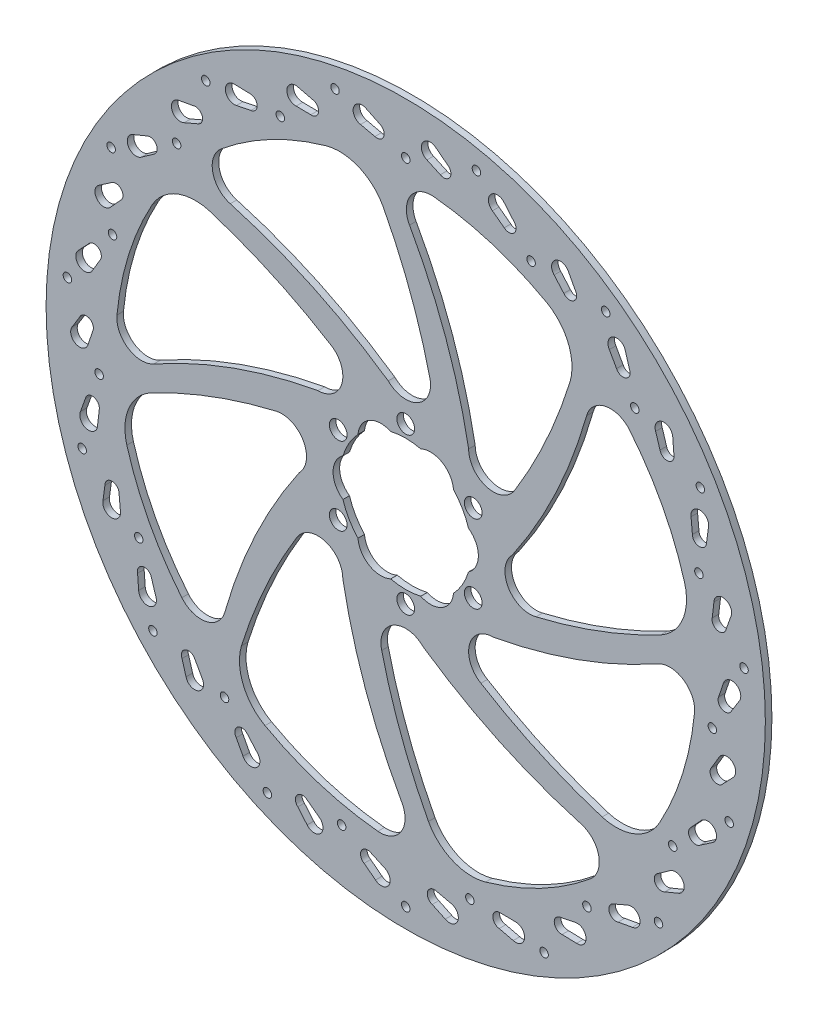
SolidWorks part; units mm, degrees
material "Chrome Stainless Steel"
ref_plane "Plan de face" through (0, 0, 0) normal (0, 0, 1) x (1, 0, 0)
ref_plane "Plan de dessus" through (0, 0, 0) normal (0, 1, 0) x (1, 0, 0)
ref_plane "Plan de droite" through (0, 0, 0) normal (1, 0, 0) x (0, 0, -1)
sketch "Sketch1" plane through (0, 0, 0) normal (0, 0, 1) x (1, 0, 0)
  line L0 (11.7494, 91.2536) -> (8.3288, 93.8934)
  line L1 (9.7648, 87.7806) -> (5.9882, 89.5132)
  line L2 (30.4653, 86.8166) -> (27.6683, 90.1099)
  line L3 (27.8021, 83.8322) -> (24.4682, 86.3121)
  line L4 (-7.48, 91.7023) -> (-11.3747, 93.5732)
  line L5 (47.8498, 78.5854) -> (45.7986, 82.3882)
  line L6 (44.6242, 76.2198) -> (41.8788, 79.3388)
  line L7 (-8.6992, 87.8926) -> (-12.7535, 88.8022)
  line L8 (63.143, 66.9196) -> (61.9273, 71.0658)
  line L9 (59.4961, 65.2764) -> (57.4591, 68.898)
  line L10 (75.6765, 52.329) -> (75.3494, 56.6374)
  line L11 (71.7677, 51.48) -> (70.5282, 55.446)
  line L12 (84.9026, 35.4515) -> (85.4784, 39.7337)
  line L13 (80.9026, 35.4337) -> (80.5148, 39.5707)
  line L14 (90.4181, 17.0245) -> (91.8716, 21.0935)
  line L15 (86.5018, 17.8388) -> (86.9826, 21.966)
  line L16 (91.9818, -2.1465) -> (94.2496, 1.5314)
  line L17 (88.3204, -0.5358) -> (89.6488, 3.4013)
  line L18 (89.5255, -21.2236) -> (92.5084, -18.0977)
  line L19 (86.279, -18.8869) -> (88.3969, -15.3121)
  line L20 (83.1565, -39.3733) -> (86.7242, -36.9358)
  line L21 (80.4668, -36.4126) -> (83.2817, -33.3562)
  line L22 (73.1532, -55.8021) -> (77.1496, -54.1596)
  line L23 (71.1378, -52.3469) -> (74.5266, -49.9425)
  line L24 (59.9527, -69.7921) -> (64.2033, -69.0164)
  line L25 (58.6997, -65.9934) -> (62.5144, -64.3461)
  line L26 (44.132, -80.7318) -> (48.451, -80.8569)
  line L27 (43.6962, -76.7556) -> (47.77, -75.9375)
  line L28 (26.3825, -88.1432) -> (30.5811, -89.1635)
  line L29 (26.783, -84.1633) -> (30.9378, -84.21)
  line L30 (7.48, -91.7023) -> (11.3747, -93.5732)
  line L31 (8.6992, -87.8926) -> (12.7535, -88.8022)
  line L32 (-11.7494, -91.2536) -> (-8.3288, -93.8934)
  line L33 (-9.7648, -87.7806) -> (-5.9882, -89.5132)
  line L34 (-30.4653, -86.8166) -> (-27.6683, -90.1099)
  line L35 (-27.8021, -83.8322) -> (-24.4682, -86.3121)
  line L36 (-47.8498, -78.5854) -> (-45.7986, -82.3882)
  line L37 (-44.6242, -76.2198) -> (-41.8788, -79.3388)
  line L38 (-63.143, -66.9196) -> (-61.9273, -71.0658)
  line L39 (-59.4961, -65.2764) -> (-57.4591, -68.898)
  line L40 (-75.6765, -52.329) -> (-75.3494, -56.6374)
  line L41 (-71.7677, -51.48) -> (-70.5282, -55.446)
  line L42 (-84.9026, -35.4515) -> (-85.4784, -39.7337)
  line L43 (-80.9026, -35.4337) -> (-80.5148, -39.5707)
  line L44 (-90.4181, -17.0245) -> (-91.8716, -21.0935)
  line L45 (-86.5018, -17.8388) -> (-86.9826, -21.966)
  line L46 (-91.9818, 2.1465) -> (-94.2496, -1.5314)
  line L47 (-88.3204, 0.5358) -> (-89.6488, -3.4013)
  line L48 (-89.5255, 21.2236) -> (-92.5084, 18.0977)
  line L49 (-86.279, 18.8869) -> (-88.3969, 15.3121)
  line L50 (-83.1565, 39.3733) -> (-86.7242, 36.9358)
  line L51 (-80.4668, 36.4126) -> (-83.2817, 33.3562)
  line L52 (-73.1532, 55.8021) -> (-77.1496, 54.1596)
  line L53 (-71.1378, 52.3469) -> (-74.5266, 49.9425)
  line L54 (-59.9527, 69.7921) -> (-64.2033, 69.0164)
  line L55 (-58.6997, 65.9934) -> (-62.5144, 64.3461)
  line L56 (-44.132, 80.7318) -> (-48.451, 80.8569)
  line L57 (-43.6962, 76.7556) -> (-47.77, 75.9375)
  line L58 (-26.3825, 88.1432) -> (-30.5811, 89.1635)
  line L59 (-26.783, 84.1633) -> (-30.9378, 84.21)
  line L60 (0, 18.97) -> (0, 25.9709) construction
  line L61 (0, 0) -> (0, 18.5) construction
  line L62 (0, 0) -> (7, 12.1244) construction
  circle A0 centre (0, 0) radius 101.5
  circle A3 centre (0, 0) radius 14 construction
  circle A4 centre (0, 0) radius 22 construction
  circle A5 centre (0, 22) radius 2.5
  circle A8 centre (19.0526, 11) radius 2.5
  arc A10 (-4.2376, 18.0081) -> (-13.4767, 12.6739) centre (-7, 12.1244) ccw
  arc A12 (13.4767, 12.6739) -> (4.2375, 18.0081) centre (7, 12.1244) ccw
  arc A13 (4.2375, 18.0081) -> (-4.2376, 18.0081) centre (0, 0) ccw
  circle A14 centre (19.0526, -11) radius 2.5
  circle A15 centre (0, -22) radius 2.5
  circle A16 centre (0, -96) radius 1.2
  circle A17 centre (-19.0526, -11) radius 2.5
  circle A18 centre (-19.0526, 11) radius 2.5
  arc A19 (17.7143, 5.3342) -> (13.4767, 12.6739) centre (0, 0) ccw
  arc A20 (-13.4767, 12.6739) -> (-17.7143, 5.3342) centre (0, 0) ccw
  arc A21 (-49.5229, 51.0449) -> (-4.9497, 30.0502) centre (-90.2856, -93.3102) cw
  arc A22 (17.7487, 24.7487) -> (30.7822, 21.1994) centre (24.7487, 24.7487) ccw
  circle A23 centre (-39.0467, -87.7004) radius 1.2
  arc A24 (-22.5455, 78.7108) -> (-52.0725, 63.1834) centre (0, 0) ccw
  arc A25 (46.3594, 55.4206) -> (39.7148, 71.599) centre (32.924, 59.3563) ccw
  arc A26 (46.3594, 55.4206) -> (30.7822, 21.1994) centre (-96.8744, 99.9637) cw
  arc A27 (7.8566, 81.4983) -> (1.0763, 71.1122) centre (7.1849, 74.5306) ccw
  arc A28 (-6.4072, 71.9693) -> (6.776, 36.7565) centre (-139.1855, 2.1845) cw
  arc A29 (39.7148, 71.599) -> (7.8566, 81.4983) centre (0, 0) ccw
  arc A30 (1.0763, 71.1122) -> (17.7487, 24.7487) centre (-129.8218, -2.1387) cw
  arc A31 (17.7143, -5.3342) -> (17.7143, 5.3342) centre (14, 0) ccw
  circle A32 centre (-71.3419, -64.2365) radius 1.2
  arc A33 (-63.1834, -52.0725) -> (-51.0449, -49.5229) centre (-57.7815, -47.6206) ccw
  arc A34 (-6.4072, 71.9693) -> (-22.5455, 78.7108) centre (-18.6905, 65.252) ccw
  arc A35 (78.7108, 22.5455) -> (63.1834, 52.0725) centre (0, 0) ccw
  arc A36 (-17.7487, -24.7487) -> (-30.7822, -21.1994) centre (-24.7487, -24.7487) ccw
  arc A37 (4.9497, -30.0503) -> (-6.776, -36.7565) centre (0, -35) ccw
  arc A38 (6.4072, -71.9693) -> (22.5455, -78.7108) centre (18.6905, -65.252) ccw
  arc A39 (6.4072, -71.9693) -> (-6.776, -36.7565) centre (139.1855, -2.1845) cw
  arc A40 (22.5455, -78.7108) -> (52.0725, -63.1834) centre (0, 0) ccw
  arc A41 (-52.0725, 63.1834) -> (-49.5229, 51.0449) centre (-47.6206, 57.7815) ccw
  arc A42 (-4.9497, 30.0502) -> (6.776, 36.7565) centre (0, 35) ccw
  arc A43 (63.1834, 52.0725) -> (51.0449, 49.5229) centre (57.7815, 47.6206) ccw
  arc A44 (13.4767, -12.6739) -> (17.7143, -5.3342) centre (0, 0) ccw
  circle A45 centre (-91.3014, -29.6656) radius 1.2
  circle A46 centre (-95.4741, 10.0347) radius 1.2
  circle A47 centre (-83.1384, 48) radius 1.2
  circle A48 centre (-56.4274, 77.6656) radius 1.2
  circle A49 centre (-19.9595, 93.9022) radius 1.2
  circle A50 centre (19.9595, 93.9022) radius 1.2
  circle A51 centre (56.4274, 77.6656) radius 1.2
  arc A52 (51.0449, 49.5229) -> (30.0502, 4.9497) centre (-93.3102, 90.2856) cw
  arc A53 (30.0502, 4.9497) -> (36.7565, -6.776) centre (35, 0) ccw
  arc A54 (71.9693, 6.4072) -> (78.7108, 22.5455) centre (65.252, 18.6905) ccw
  arc A55 (4.2376, -18.0081) -> (13.4767, -12.6739) centre (7, -12.1244) ccw
  arc A56 (71.9693, 6.4072) -> (36.7565, -6.776) centre (2.1845, 139.1855) cw
  arc A57 (55.4206, -46.3594) -> (71.599, -39.7148) centre (59.3563, -32.924) ccw
  arc A58 (55.4206, -46.3594) -> (21.1994, -30.7822) centre (99.9637, 96.8744) cw
  arc A59 (24.7487, -17.7487) -> (21.1994, -30.7822) centre (24.7487, -24.7487) ccw
  arc A60 (81.4983, -7.8566) -> (71.1122, -1.0763) centre (74.5306, -7.1849) ccw
  arc A61 (71.599, -39.7148) -> (81.4983, -7.8566) centre (0, 0) ccw
  arc A62 (71.1122, -1.0763) -> (24.7487, -17.7487) centre (-2.1387, 129.8218) cw
  arc A63 (-4.2376, -18.0081) -> (4.2376, -18.0081) centre (0, 0) ccw
  circle A64 centre (83.1384, 48) radius 1.2
  circle A65 centre (95.4741, 10.0347) radius 1.2
  circle A66 centre (91.3014, -29.6656) radius 1.2
  circle A67 centre (71.3419, -64.2365) radius 1.2
  circle A68 centre (39.0467, -87.7004) radius 1.2
  arc A69 (-55.4206, 46.3594) -> (-21.1994, 30.7821) centre (-99.9637, -96.8744) cw
  arc A70 (-71.599, 39.7148) -> (-81.4983, 7.8566) centre (0, 0) ccw
  arc A71 (-71.9693, -6.4072) -> (-78.7108, -22.5455) centre (-65.252, -18.6905) ccw
  arc A72 (-24.7487, 17.7487) -> (-21.1994, 30.7821) centre (-24.7487, 24.7487) ccw
  circle A73 centre (18.0883, -85.0988) radius 1.2
  arc A74 (49.5229, -51.045) -> (4.9497, -30.0503) centre (90.2856, 93.3102) cw
  arc A75 (-13.4767, -12.6739) -> (-4.2376, -18.0081) centre (-7, -12.1244) ccw
  arc A76 (52.0725, -63.1834) -> (49.5229, -51.045) centre (47.6206, -57.7815) ccw
  arc A77 (-46.3594, -55.4206) -> (-30.7822, -21.1994) centre (96.8744, -99.9637) cw
  arc A78 (-46.3594, -55.4206) -> (-39.7148, -71.599) centre (-32.924, -59.3563) ccw
  arc A79 (-39.7148, -71.599) -> (-7.8566, -81.4983) centre (0, 0) ccw
  arc A80 (-1.0763, -71.1122) -> (-17.7487, -24.7487) centre (129.8218, 2.1387) cw
  arc A81 (-7.8566, -81.4983) -> (-1.0763, -71.1122) centre (-7.1849, -74.5306) ccw
  arc A82 (-17.7143, -5.3342) -> (-13.4767, -12.6739) centre (0, 0) ccw
  arc A83 (-78.7108, -22.5455) -> (-63.1834, -52.0725) centre (0, 0) ccw
  arc A84 (-71.9693, -6.4072) -> (-36.7565, 6.776) centre (-2.1845, -139.1855) cw
  arc A85 (-51.0449, -49.5229) -> (-30.0502, -4.9497) centre (93.3102, -90.2856) cw
  arc A86 (-30.0502, -4.9497) -> (-36.7565, 6.776) centre (-35, 0) ccw
  arc A87 (-17.7143, 5.3342) -> (-17.7143, -5.3342) centre (-14, 0) ccw
  arc A88 (-81.4983, 7.8566) -> (-71.1122, 1.0763) centre (-74.5306, 7.1849) ccw
  arc A89 (-55.4206, 46.3594) -> (-71.599, 39.7148) centre (-59.3563, 32.924) ccw
  arc A91 (-71.1122, 1.0763) -> (-24.7487, 17.7487) centre (2.1387, -129.8218) cw
  circle A92 centre (-18.0883, -85.0988) radius 1.2
  circle A93 centre (-51.1373, -70.3845) radius 1.2
  circle A94 centre (-75.3442, -43.5) radius 1.2
  circle A95 centre (-86.5234, -9.094) radius 1.2
  circle A96 centre (-82.7419, 26.8845) radius 1.2
  circle A97 centre (-64.6536, 58.2144) radius 1.2
  circle A98 centre (-35.3861, 79.4785) radius 1.2
  circle A99 centre (0, 87) radius 1.2
  circle A100 centre (35.3861, 79.4785) radius 1.2
  circle A101 centre (64.6536, 58.2144) radius 1.2
  circle A102 centre (82.7419, 26.8845) radius 1.2
  circle A103 centre (86.5234, -9.094) radius 1.2
  circle A104 centre (75.3442, -43.5) radius 1.2
  circle A105 centre (51.1373, -70.3845) radius 1.2
  arc A106 (9.7648, 87.7806) -> (11.7494, 91.2536) centre (10.7571, 89.5171) ccw
  arc A107 (-8.6992, 87.8926) -> (-7.48, 91.7023) centre (-8.0896, 89.7975) ccw
  arc A108 (-11.1479, 93.4643) -> (-12.7535, 88.8022) centre (-12.3425, 91.2681) ccw
  arc A109 (8.528, 93.7396) -> (5.9882, 89.5132) centre (6.9029, 91.8399) ccw
  arc A110 (27.8021, 83.8322) -> (30.4653, 86.8166) centre (29.1337, 85.3244) ccw
  arc A111 (27.8312, 89.9181) -> (24.4682, 86.3121) centre (25.8467, 88.3977) ccw
  arc A112 (44.6242, 76.2198) -> (47.8498, 78.5854) centre (46.237, 77.4026) ccw
  arc A113 (45.9181, 82.1668) -> (41.8788, 79.3388) centre (43.6608, 81.0922) ccw
  arc A114 (59.4961, 65.2764) -> (63.143, 66.9196) centre (61.3195, 66.098) ccw
  arc A115 (61.9981, 70.8243) -> (57.4591, 68.898) centre (59.5667, 70.2426) ccw
  arc A116 (71.7677, 51.48) -> (75.6765, 52.329) centre (73.7221, 51.9045) ccw
  arc A117 (75.3685, 56.3865) -> (70.5282, 55.446) centre (72.8693, 56.323) ccw
  arc A118 (80.9026, 35.4337) -> (84.9026, 35.4515) centre (82.9026, 35.4426) ccw
  arc A119 (85.4449, 39.4844) -> (80.5148, 39.5707) centre (82.9871, 39.9418) ccw
  arc A120 (86.5018, 17.8388) -> (90.4181, 17.0245) centre (88.4599, 17.4317) ccw
  arc A121 (91.787, 20.8565) -> (86.9826, 21.966) centre (89.478, 21.815) ccw
  arc A122 (88.3204, -0.5358) -> (91.9818, -2.1465) centre (90.1511, -1.3411) ccw
  arc A123 (94.1175, 1.3172) -> (89.6488, 3.4013) centre (92.0583, 2.7347) ccw
  arc A124 (86.279, -18.8869) -> (89.5255, -21.2236) centre (87.9023, -20.0553) ccw
  arc A125 (92.3347, -18.2797) -> (88.3969, -15.3121) centre (90.6152, -16.465) ccw
  arc A126 (80.4668, -36.4126) -> (83.1565, -39.3733) centre (81.8117, -37.8929) ccw
  arc A127 (86.5164, -37.0778) -> (83.2817, -33.3562) centre (85.2118, -34.9452) ccw
  arc A128 (71.1378, -52.3469) -> (73.1532, -55.8021) centre (72.1455, -54.0745) ccw
  arc A129 (76.9169, -54.2553) -> (74.5266, -49.9425) centre (76.0842, -51.8981) ccw
  arc A130 (58.6997, -65.9934) -> (59.9527, -69.7921) centre (59.3262, -67.8927) ccw
  arc A131 (63.9558, -69.0616) -> (62.5144, -64.3461) centre (63.6313, -66.5827) ccw
  arc A132 (43.6962, -76.7556) -> (44.132, -80.7318) centre (43.9141, -78.7437) ccw
  arc A133 (48.1995, -80.8496) -> (47.77, -75.9375) centre (48.3975, -78.3575) ccw
  arc A134 (26.783, -84.1633) -> (26.3825, -88.1432) centre (26.5828, -86.1532) ccw
  arc A135 (30.3366, -89.1041) -> (30.9378, -84.21) centre (31.0485, -86.7076) ccw
  arc A136 (8.6992, -87.8926) -> (7.48, -91.7023) centre (8.0896, -89.7975) ccw
  arc A137 (11.1479, -93.4643) -> (12.7535, -88.8022) centre (12.3425, -91.2681) ccw
  arc A138 (-9.7648, -87.7806) -> (-11.7494, -91.2536) centre (-10.7571, -89.5171) ccw
  arc A139 (-8.528, -93.7396) -> (-5.9882, -89.5132) centre (-6.9029, -91.8399) ccw
  arc A140 (-27.8021, -83.8322) -> (-30.4653, -86.8166) centre (-29.1337, -85.3244) ccw
  arc A141 (-27.8312, -89.9181) -> (-24.4682, -86.3121) centre (-25.8467, -88.3977) ccw
  arc A142 (-44.6242, -76.2198) -> (-47.8498, -78.5854) centre (-46.237, -77.4026) ccw
  arc A143 (-45.9181, -82.1668) -> (-41.8788, -79.3388) centre (-43.6608, -81.0922) ccw
  arc A144 (-59.4961, -65.2764) -> (-63.143, -66.9196) centre (-61.3195, -66.098) ccw
  arc A145 (-61.9981, -70.8243) -> (-57.4591, -68.898) centre (-59.5667, -70.2426) ccw
  arc A146 (-71.7677, -51.48) -> (-75.6765, -52.329) centre (-73.7221, -51.9045) ccw
  arc A147 (-75.3685, -56.3865) -> (-70.5282, -55.446) centre (-72.8693, -56.323) ccw
  arc A148 (-80.9026, -35.4337) -> (-84.9026, -35.4515) centre (-82.9026, -35.4426) ccw
  arc A149 (-85.4449, -39.4844) -> (-80.5148, -39.5707) centre (-82.9871, -39.9418) ccw
  arc A150 (-86.5018, -17.8388) -> (-90.4181, -17.0245) centre (-88.4599, -17.4317) ccw
  arc A151 (-91.787, -20.8565) -> (-86.9826, -21.966) centre (-89.478, -21.815) ccw
  arc A152 (-88.3204, 0.5358) -> (-91.9818, 2.1465) centre (-90.1511, 1.3411) ccw
  arc A153 (-94.1175, -1.3172) -> (-89.6488, -3.4013) centre (-92.0583, -2.7347) ccw
  arc A154 (-86.279, 18.8869) -> (-89.5255, 21.2236) centre (-87.9023, 20.0553) ccw
  arc A155 (-92.3347, 18.2797) -> (-88.3969, 15.3121) centre (-90.6152, 16.465) ccw
  arc A156 (-80.4668, 36.4126) -> (-83.1565, 39.3733) centre (-81.8117, 37.8929) ccw
  arc A157 (-86.5164, 37.0778) -> (-83.2817, 33.3562) centre (-85.2118, 34.9452) ccw
  arc A158 (-71.1378, 52.3469) -> (-73.1532, 55.8021) centre (-72.1455, 54.0745) ccw
  arc A159 (-76.9169, 54.2553) -> (-74.5266, 49.9425) centre (-76.0842, 51.8981) ccw
  arc A160 (-58.6997, 65.9934) -> (-59.9527, 69.7921) centre (-59.3262, 67.8927) ccw
  arc A161 (-63.9558, 69.0616) -> (-62.5144, 64.3461) centre (-63.6313, 66.5827) ccw
  arc A162 (-43.6962, 76.7556) -> (-44.132, 80.7318) centre (-43.9141, 78.7437) ccw
  arc A163 (-48.1995, 80.8496) -> (-47.77, 75.9375) centre (-48.3975, 78.3575) ccw
  arc A164 (-26.783, 84.1633) -> (-26.3825, 88.1432) centre (-26.5828, 86.1532) ccw
  arc A165 (-30.3366, 89.1041) -> (-30.9378, 84.21) centre (-31.0485, 86.7076) ccw
  dimension "D2" = 6
  dimension "D3" = 44
  dimension "D4" = 37
  dimension "D6" = 30
extrude "Extrude1" add sketch "Sketch1" along normal blind 1.85 contours A0 A165 L58 A164 L59 A163 L56 A162 L57 A161 L54 A160 L55 A159 L52 A158 L53 A157 L50 A156 L51 A155 L48 A154 L49 A153 L46 A152 L47 A151 L44 A150 L45 A149
